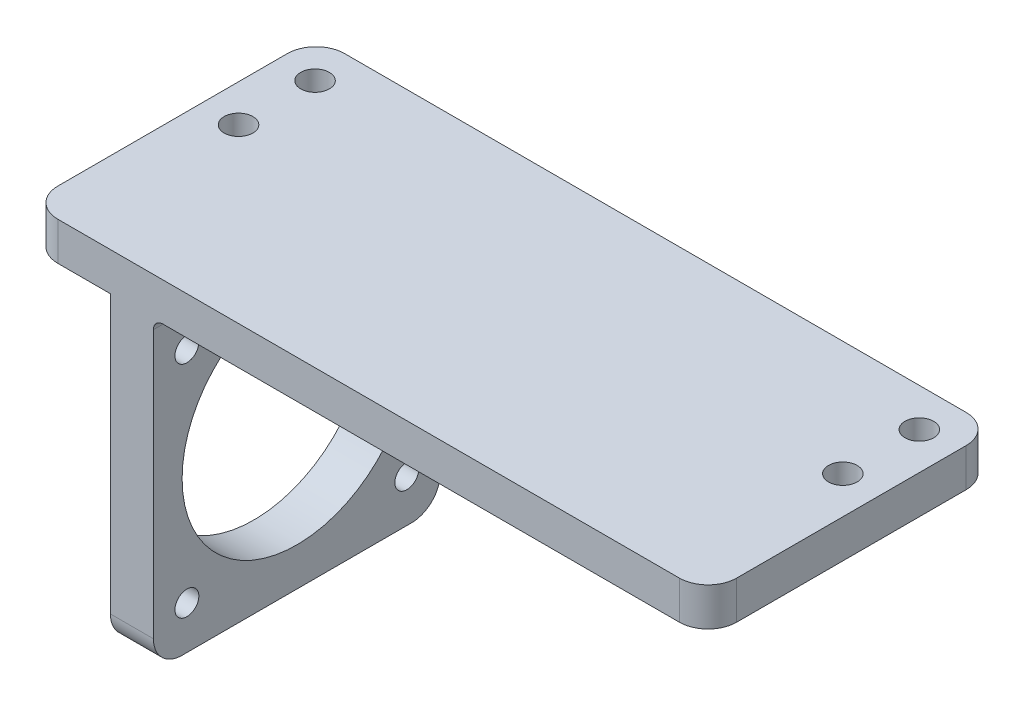
SolidWorks part; units mm, degrees
material "聚脂树脂"
ref_plane "前视基准面" through (0, 0, 0) normal (0, 0, 1) x (1, 0, 0)
ref_plane "上视基准面" through (0, 0, 0) normal (0, 1, 0) x (1, 0, 0)
ref_plane "右视基准面" through (0, 0, 0) normal (1, 0, 0) x (0, 0, -1)
other "Configuration Table"
sketch "草图1" plane through (0, 0, 0) normal (0, 1, 0) x (1, 0, 0)
  line L0 (0, 0) -> (0, 26.3912) construction
  line L1 (-35.5, -15) -> (35.5, -15)
  line L2 (-35.5, -15) -> (-35.5, 15)
  line L3 (-35.5, 15) -> (35.5, 15)
  line L4 (35.5, -15) -> (35.5, 15)
  line L5 (-35.5, -15) -> (35.5, 15) construction
  line L6 (-35.5, 15) -> (35.5, -15) construction
  line L7 (0, 0) -> (47.2738, 0) construction
  line L8 (0, 7) -> (45.2501, 7) construction
  circle A0 centre (31.6, 11) radius 1.5
  circle A2 centre (31.6, 3) radius 1.5
  circle A3 centre (-31.6, 3) radius 1.5
  circle A4 centre (-31.6, 11) radius 1.5
  point P0 (0, 0)
  dimension "D3" = 3
  dimension "D4" = 8
  dimension "D5" = 63.2
  dimension "D1" = 71
  dimension "D2" = 30
  dimension "D6" = 7
extrude "凸台-拉伸1" add sketch "草图1" along normal blind 4
fillet "圆角1" radius 3 4 edges at (-35.5, 2, -15) (-35.5, 2, 15) (35.5, 2, -15) (35.5, 2, 15)
sketch "草图3" plane through (0, 0, 0) normal (0, -1, 0) x (1, 0, 0)
  line L0 (0, 0) -> (0, -24.947) construction
  line L1 (0, 0) -> (-45.8966, 0) construction
  line L2 (-27, 15) -> (-27, -15)
  line L3 (32.5, -15) -> (-32.5, -15) construction
  line L4 (-27, -15) -> (-22.5, -15)
  line L5 (-22.5, -15) -> (-22.5, 15)
  line L6 (-27, 15) -> (-22.5, 15)
  point P11 (-22.5, 0)
  point P12 (-27, 0)
  dimension "D1" = 4.5
  dimension "D2" = 22.5
extrude "凸台-拉伸3" add sketch "草图3" along normal blind 32
sketch "草图4" plane through (-27, 0, 0) normal (-1, 0, 0) x (0, 0, 1)
  line L0 (0, 0) -> (0, -31.6027) construction
  line L1 (0, -16) -> (21.235, -16) construction
  line L2 (15, 0) -> (-15, 0) construction
  circle A0 centre (11.5, -4.5) radius 1.25
  circle A1 centre (11.5, -27.5) radius 1.25
  circle A2 centre (-11.5, -27.5) radius 1.25
  circle A3 centre (-11.5, -4.5) radius 1.25
  circle A4 centre (0, -16) radius 12
  dimension "D1" = 23
  dimension "D2" = 2.5
  dimension "D3" = 23
  dimension "D5" = 24
  dimension "D4" = 16
extrude "切除-拉伸1" cut sketch "草图4" against normal blind 30
fillet "圆角2" radius 3 2 edges at (-24.75, -32, -15) (-24.75, -32, 15)
fillet "圆角3" radius 1 1 edges at (-22.5, 0, 0)
